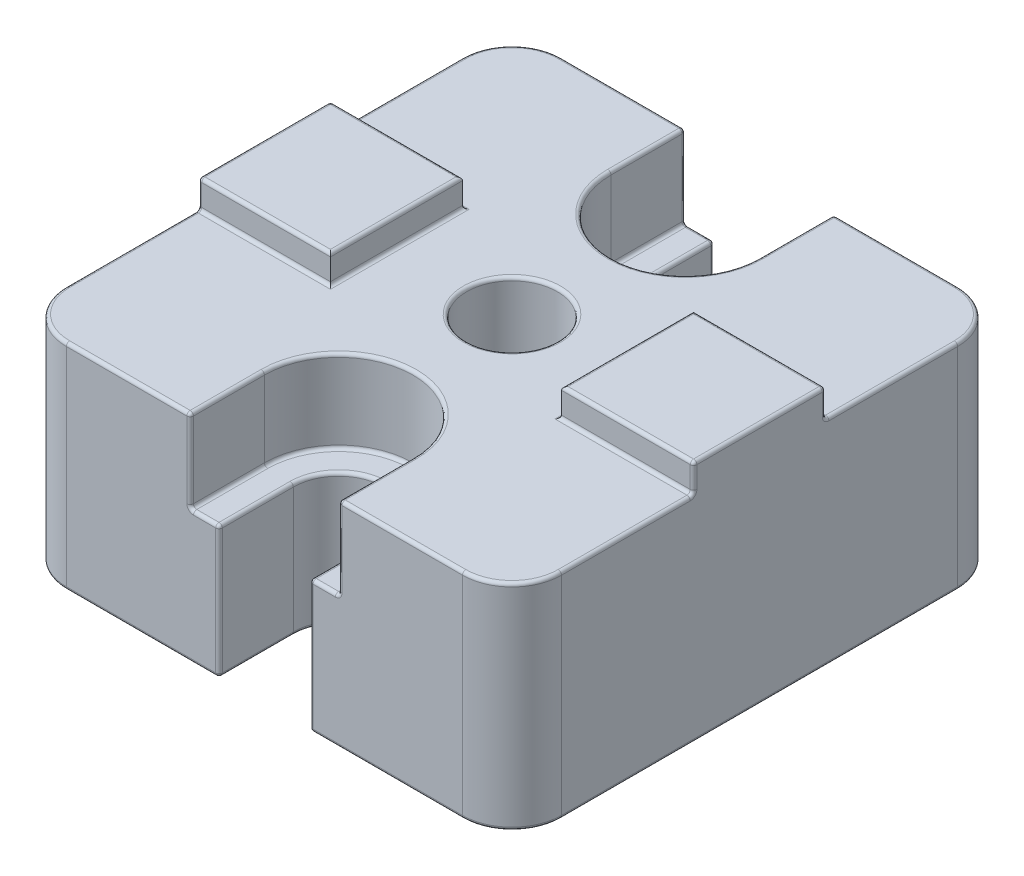
SolidWorks part; units mm, degrees
ref_plane "Front Plane" through (0, 0, 0) normal (0, 0, 1) x (1, 0, 0)
ref_plane "Top Plane" through (0, 0, 0) normal (0, 1, 0) x (1, 0, 0)
ref_plane "Right Plane" through (0, 0, 0) normal (1, 0, 0) x (0, 0, -1)
sketch "Sketch1" plane through (0, 0, 0) normal (0, 1, 0) x (1, 0, 0)
  line L0 (2.75, -10.5) -> (2.75, -14.8)
  line L1 (-2.75, -14.8) -> (-2.75, -10.5)
  line L2 (-12, -15) -> (-2.95, -15)
  line L3 (-15, 12) -> (-15, -12)
  line L4 (2.95, -15) -> (12, -15)
  line L5 (15, -12) -> (15, 12)
  line L6 (12, 15) -> (2.95, 15)
  line L7 (2.75, 14.8) -> (2.75, 10.5)
  line L8 (-2.75, 10.5) -> (-2.75, 14.8)
  line L9 (-2.95, 15) -> (-12, 15)
  line L10 (0, 7.75) -> (0, -7.75) construction
  arc A0 (2.75, -14.8) -> (2.95, -15) centre (2.95, -14.8) ccw
  arc A1 (2.75, -10.5) -> (-2.75, -10.5) centre (0, -10.5) ccw
  arc A2 (-2.95, -15) -> (-2.75, -14.8) centre (-2.95, -14.8) ccw
  arc A3 (-15, -12) -> (-12, -15) centre (-12, -12) ccw
  arc A4 (12, -15) -> (15, -12) centre (12, -12) ccw
  arc A5 (15, 12) -> (12, 15) centre (12, 12) ccw
  arc A6 (2.95, 15) -> (2.75, 14.8) centre (2.95, 14.8) ccw
  arc A7 (-2.75, 10.5) -> (2.75, 10.5) centre (0, 10.5) ccw
  arc A8 (-2.75, 14.8) -> (-2.95, 15) centre (-2.95, 14.8) ccw
  arc A9 (-12, 15) -> (-15, 12) centre (-12, 12) ccw
extrude "Boss-Extrude1" add sketch "Sketch1" along normal blind 13 contours L3 A3 L2 A2 L1 A1 L0 A0 L4 A4 L5 A5 L6 A6 L7 A7 L8 A8 L9 A9
sketch "Sketch2" plane through (0, 13, 0) normal (0, 1, 0) x (1, 0, 0)
  line L0 (7.2, 4) -> (14.8, 4)
  line L1 (7, -3.8) -> (7, 4)
  line L2 (7.2, 4) -> (7, 4)
  line L3 (15, -3.8) -> (15, 4)
  line L4 (14.8, 4) -> (15, 4)
  line L5 (15, -4) -> (7, -4)
  line L6 (7, -3.8) -> (7, -4)
  line L7 (15, -3.8) -> (15, -4)
  line L8 (0, 0) -> (7, 0.1) construction
extrude "Boss-Extrude2" add sketch "Sketch2" along normal blind 1.7
mirror "Mirror1" about plane through (0, 0, 0) normal (1, 0, 0) of "Boss-Extrude2"
sketch "Sketch3" plane through (0, 13, 0) normal (0, 1, 0) x (1, 0, 0)
  line L0 (-2.75, 10.5) -> (-2.75, 14.8) construction
  line L1 (2.75, 14.8) -> (2.75, 10.5) construction
  line L2 (-2.75, 10.5) -> (-2.75, 14.8) construction
  line L3 (2.75, 14.8) -> (2.75, 10.5) construction
  line L4 (4.5, 14.8) -> (4.5, 10.5)
  line L5 (-4.5, 10.5) -> (-4.5, 14.8)
  line L6 (4.5, 14.8) -> (4.5, 15)
  line L7 (12, 15) -> (2.95, 15) construction
  line L8 (-4.5, 14.8) -> (-4.5, 15)
  line L9 (-2.95, 15) -> (-12, 15) construction
  line L10 (-4.5, 15) -> (4.5, 15)
  arc A0 (-2.75, 10.5) -> (2.75, 10.5) centre (0, 10.5) ccw construction
  arc A1 (-2.75, 10.5) -> (2.75, 10.5) centre (0, 10.5) ccw construction
  arc A2 (-4.5, 10.5) -> (4.5, 10.5) centre (0, 10.5) ccw
  dimension "D1" = 1.75
extrude "Cut-Extrude1" cut sketch "Sketch3" against normal blind 5
mirror "Mirror2" about plane through (0, 0, 0) normal (0, 0, 1) of "Cut-Extrude1"
sketch "Sketch4" plane through (0, 13, 0) normal (0, 1, 0) x (1, 0, 0)
  circle A0 centre (0, 0) radius 2.75
  dimension "D1" = 5.5
extrude "Cut-Extrude2" cut sketch "Sketch4" against normal blind 35
sketch "Sketch5" plane through (0, 0, 0) normal (0, -1, 0) x (1, 0, 0)
  circle A0 centre (0, 0) radius 4.6
  dimension "D1" = 9.2
extrude "Cut-Extrude3" cut sketch "Sketch5" against normal blind 6
fillet "Fillet1" radius 0.2 81 edges at (0, 8, -7.75) (-4.5, 13, -12.75) (0, 13, -6) (4.5, 13, -12.75) (-3.725, 8, -15) (-4.5, 10.5, -15) (4.5, 8, -12.75) (4.5, 10.5, -15) (0, 8, -6) (-4.5, 8, -12.75) (3.725, 8, -15) (2.8086, 8, -14.9414) (2.75, 8, -12.65) (-2.75, 8, -12.65) (-2.8086, 8, -14.9414) (8.25, 13, 15) (-14.1213, 13, 14.1213) (-3.725, 8, 15) (-4.5, 8, 12.75) (0, 8, 6) (4.5, 8, 12.75) (3.725, 8, 15) (0, 8, 7.75) (4.5, 10.5, 15) (-4.5, 13, 12.75) (-4.5, 10.5, 15) (0, 13, 6) (4.5, 13, 12.75) (-2.8086, 8, 14.9414) (-2.75, 8, 12.65) (2.75, 8, 12.65) (2.8086, 8, 14.9414) (0, 13, 2.75) (-8.25, 13, 15) (-7.475, 0, -15) (-2.8086, 0, -14.9414) (-2.75, 0, -12.65) (0, 0, -7.75) (2.75, 0, -12.65) (2.8086, 0, -14.9414) (7.475, 0, -15) (14.1213, 0, -14.1213) (15, 0, 0) (14.1213, 0, 14.1213) (7.475, 0, 15) (2.8086, 0, 14.9414) (2.75, 0, 12.65) (0, 0, 7.75) (-2.75, 0, 12.65) (-2.8086, 0, 14.9414) (-7.475, 0, 15) (-14.1213, 0, 14.1213) (-15, 0, 0) (-14.1213, 0, -14.1213) (14.1213, 13, 14.1213) (15, 13, 8) (-14.1213, 13, -14.1213) (14.1213, 13, -14.1213) (8.25, 13, -15) (15, 13, -8) (7, 13, 0) (11, 13, 4) (15, 13.85, 4) (11, 13, -4) (15, 13.85, -4) (11, 14.7, -4) (7, 14.7, 0) (11, 14.7, 4) (15, 14.7, 0) (-15, 13, 8) (-11, 14.7, -4) (-15, 14.7, 0) (-15, 13.85, -4) (-11, 14.7, 4) (-15, 13.85, 4) (-7, 14.7, 0) (-11, 13, -4) (-7, 13, 0) (-11, 13, 4) (-15, 13, -8) (-8.25, 13, -15)
